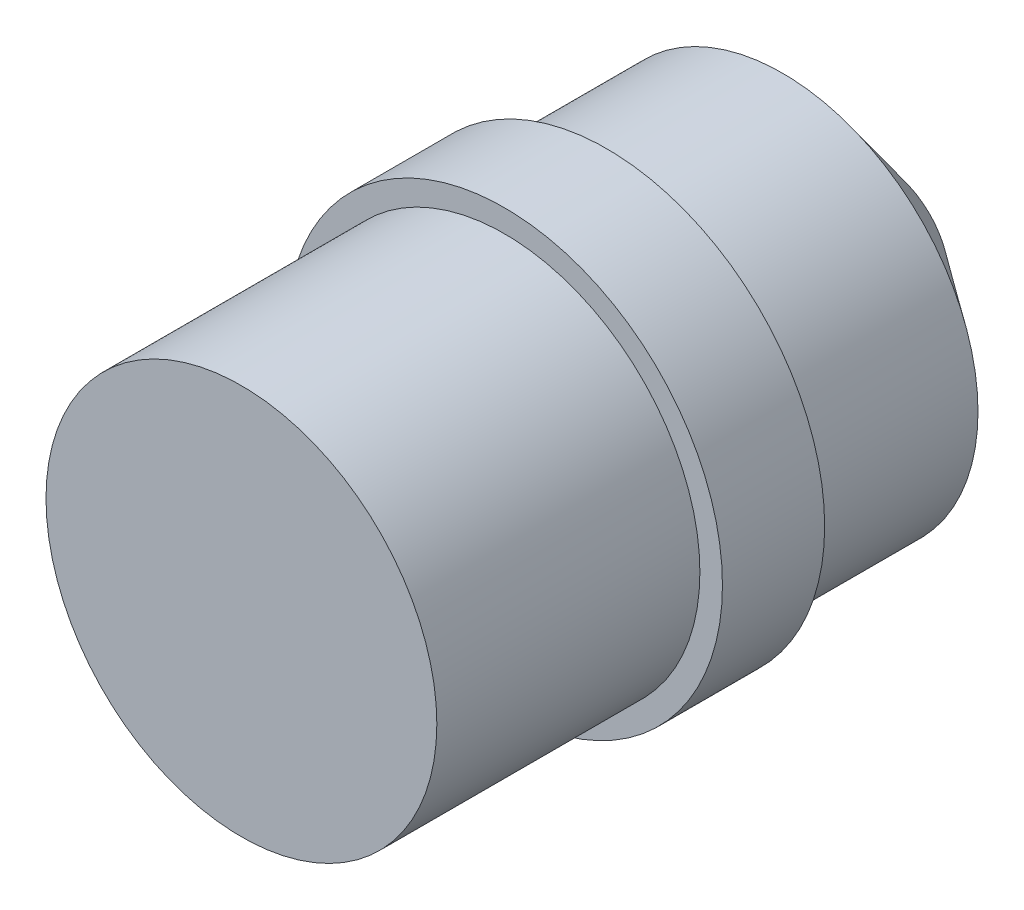
SolidWorks part; units mm, degrees
ref_plane "前基準面" through (0, 0, 0) normal (0, 0, 1) x (1, 0, 0)
ref_plane "上基準面" through (0, 0, 0) normal (0, 1, 0) x (1, 0, 0)
ref_plane "右基準面" through (0, 0, 0) normal (1, 0, 0) x (0, 0, -1)
sketch "草圖1" plane through (0, 0, 0) normal (0, 0, 1) x (1, 0, 0)
  circle A0 centre (0, 0) radius 14.5
  dimension "D1" = 29
extrude "填料-伸長1" add sketch "草圖1" along normal blind 42.6
sketch "草圖3" plane through (0, 0, 0) normal (0, 1, 0) x (1, 0, 0)
  line L0 (0, 0) -> (0, -42.6) construction
  line L1 (-14.5, -42.6) -> (14.5, -42.6) construction
  line L2 (0, 0) -> (-4.5, 0) construction
  line L3 (14.5, 0) -> (-14.5, 0) construction
  line L4 (-4.5, 0) -> (-13, -6.6)
  line L6 (-14.5, 0) -> (-4.5, 0)
  line L7 (-13, -6.6) -> (-13, -42.6) construction
  line L8 (-14.5, -42.6) -> (-14.5, -18.3) construction
  line L9 (-14.5, 0) -> (-14.5, -42.6) construction
  line L10 (-14.5, -42.6) -> (-14.5, -25.1) construction
  line L11 (-13, -6.6) -> (-13, -18.3)
  line L12 (-13, -18.3) -> (-14.5, -18.3)
  line L13 (-14.5, -25.1) -> (-14.5, -42.6)
  line L14 (-14.5, -25.1) -> (-13, -25.1)
  line L15 (-14.5, 0) -> (-14.5, -18.3)
  line L16 (-13, -25.1) -> (-13, -42.6)
  line L17 (-14.5, -42.6) -> (-13, -42.6)
  dimension "D1" = 4.5
  dimension "D2" = 1.5
  dimension "D3" = 36
  dimension "D4" = 24.3
  dimension "D5" = 17.5
revolve "除料-旋轉1" cut sketch "草圖3" angle 360 about L0
